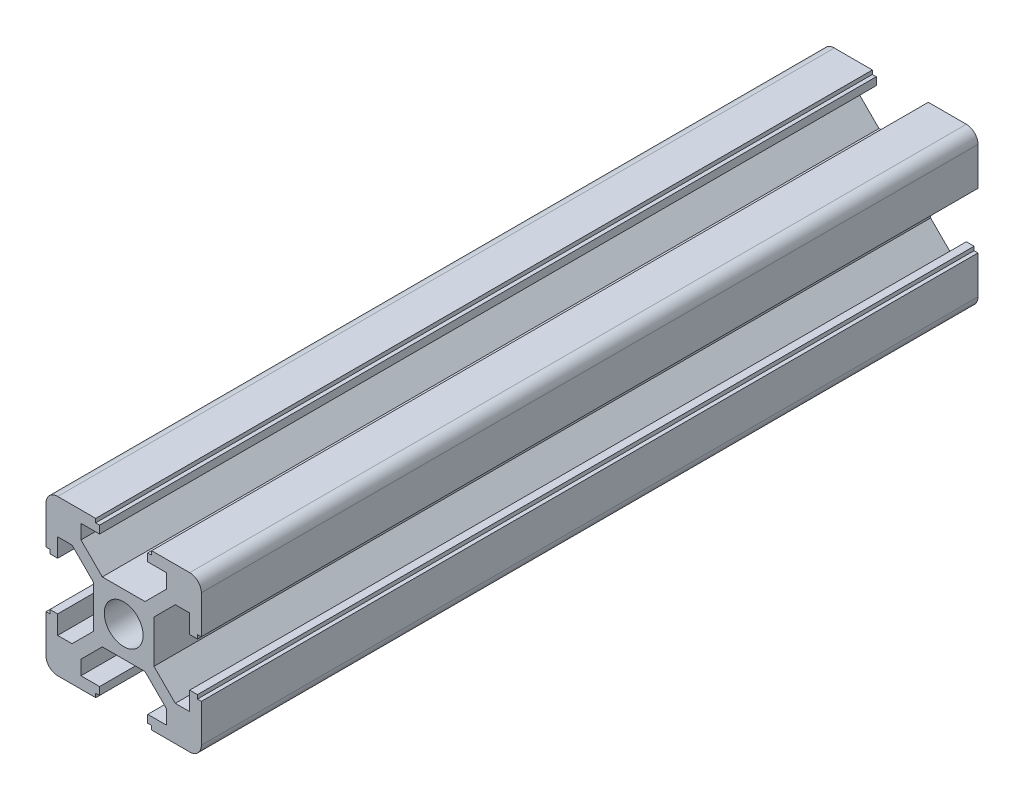
SolidWorks part; units mm, degrees
ref_plane "前视基准面" through (0, 0, 0) normal (0, 0, 1) x (1, 0, 0)
ref_plane "上视基准面" through (0, 0, 0) normal (0, 1, 0) x (1, 0, 0)
ref_plane "右视基准面" through (0, 0, 0) normal (1, 0, 0) x (0, 0, -1)
other "Configuration Table"
sketch "草图1" plane through (0, 0, 0) normal (1, 0, 0) x (0, 0, -1)
  line L0 (0, 0) -> (100, 0)
  dimension "D1" = 100
other "铝型材 20 X 20 X R1.5(1)"
ref_plane "基准面1" through (0, 0, 0) normal (0, 0, -1) x (0, 1, 0)
sketch "Sketch1" plane through (0, 0, 0) normal (0, 0, -1) x (0, 1, 0)
  line L0 (-3.6, 10) -> (-3.6, 9.5)
  line L1 (-3.6, 9.5) -> (-3.1, 9.5)
  line L2 (-3.1, 9.5) -> (-3.1, 8.5)
  line L3 (-3.1, 8.5) -> (-5.5, 8.5)
  line L4 (-8.5, -10) -> (-3.6, -10)
  line L5 (-10, -8.5) -> (-10, -3.6)
  line L6 (8.5, 10) -> (3.6, 10)
  line L7 (10, 8.5) -> (10, 3.6)
  line L8 (0, 14.8756) -> (0, 0) construction
  line L9 (0, 0) -> (14.1675, 0) construction
  line L10 (-5.5, 8.5) -> (-5.5, 6.65)
  line L11 (-5.5, 6.65) -> (-2.75, 3.9)
  line L12 (-2.75, 3.9) -> (2.75, 3.9)
  line L13 (5.5, 6.65) -> (2.75, 3.9)
  line L14 (5.5, 8.5) -> (5.5, 6.65)
  line L15 (3.1, 8.5) -> (5.5, 8.5)
  line L16 (3.1, 9.5) -> (3.1, 8.5)
  line L17 (3.6, 9.5) -> (3.1, 9.5)
  line L18 (3.6, 10) -> (3.6, 9.5)
  line L19 (-3.6, 10) -> (-8.5, 10)
  line L20 (10, 3.6) -> (9.5, 3.6)
  line L21 (9.5, 3.6) -> (9.5, 3.1)
  line L22 (9.5, 3.1) -> (8.5, 3.1)
  line L23 (8.5, 3.1) -> (8.5, 5.5)
  line L24 (8.5, 5.5) -> (6.65, 5.5)
  line L25 (6.65, 5.5) -> (3.9, 2.75)
  line L26 (3.9, 2.75) -> (3.9, -2.75)
  line L27 (6.65, -5.5) -> (3.9, -2.75)
  line L28 (8.5, -5.5) -> (6.65, -5.5)
  line L29 (8.5, -3.1) -> (8.5, -5.5)
  line L30 (9.5, -3.1) -> (8.5, -3.1)
  line L31 (9.5, -3.6) -> (9.5, -3.1)
  line L32 (10, -3.6) -> (9.5, -3.6)
  line L33 (3.6, -10) -> (3.6, -9.5)
  line L34 (3.6, -9.5) -> (3.1, -9.5)
  line L35 (3.1, -9.5) -> (3.1, -8.5)
  line L36 (3.1, -8.5) -> (5.5, -8.5)
  line L37 (5.5, -8.5) -> (5.5, -6.65)
  line L38 (5.5, -6.65) -> (2.75, -3.9)
  line L39 (2.75, -3.9) -> (-2.75, -3.9)
  line L40 (-5.5, -6.65) -> (-2.75, -3.9)
  line L41 (-5.5, -8.5) -> (-5.5, -6.65)
  line L42 (-3.1, -8.5) -> (-5.5, -8.5)
  line L43 (-3.1, -9.5) -> (-3.1, -8.5)
  line L44 (-3.6, -9.5) -> (-3.1, -9.5)
  line L45 (-3.6, -10) -> (-3.6, -9.5)
  line L46 (-10, -3.6) -> (-9.5, -3.6)
  line L47 (-9.5, -3.6) -> (-9.5, -3.1)
  line L48 (-9.5, -3.1) -> (-8.5, -3.1)
  line L49 (-8.5, -3.1) -> (-8.5, -5.5)
  line L50 (-8.5, -5.5) -> (-6.65, -5.5)
  line L51 (-6.65, -5.5) -> (-3.9, -2.75)
  line L52 (-3.9, -2.75) -> (-3.9, 2.75)
  line L53 (-6.65, 5.5) -> (-3.9, 2.75)
  line L54 (-8.5, 5.5) -> (-6.65, 5.5)
  line L55 (-8.5, 3.1) -> (-8.5, 5.5)
  line L56 (-9.5, 3.1) -> (-8.5, 3.1)
  line L57 (-9.5, 3.6) -> (-9.5, 3.1)
  line L58 (-10, 3.6) -> (-9.5, 3.6)
  line L59 (3.6, -10) -> (8.5, -10)
  line L60 (-10, 3.6) -> (-10, 8.5)
  line L61 (10, -3.6) -> (10, -8.5)
  circle A0 centre (0, 0) radius 2.5
  arc A1 (-10, 8.5) -> (-8.5, 10) centre (-8.5, 8.5) cw
  arc A2 (10, 8.5) -> (8.5, 10) centre (8.5, 8.5) ccw
  arc A3 (-8.5, -10) -> (-10, -8.5) centre (-8.5, -8.5) cw
  arc A4 (8.5, -10) -> (10, -8.5) centre (8.5, -8.5) ccw
  point P0 (-10, 0)
  point P1 (10, 0)
  point P2 (0, 10)
  point P3 (0, -10)
  point P4 (0, 0)
  point P5 (-10, -10)
  point P6 (10, -10)
  point P7 (10, 10)
  point P8 (-10, 10)
  point P13 (0, 0)
  point P36 (-10, 10)
  point P39 (10, 10)
  dimension "D1" = 11
  dimension "D2" = 20
  dimension "D3" = 6.2
  dimension "D4" = 7.2
  dimension "D5" = 6.1
  dimension "D6" = 5
  dimension "D7" = 1.5
  dimension "D8" = 45
  dimension "D9" = 0.5
  dimension "D10" = 1
  dimension "D11" = 5.5
